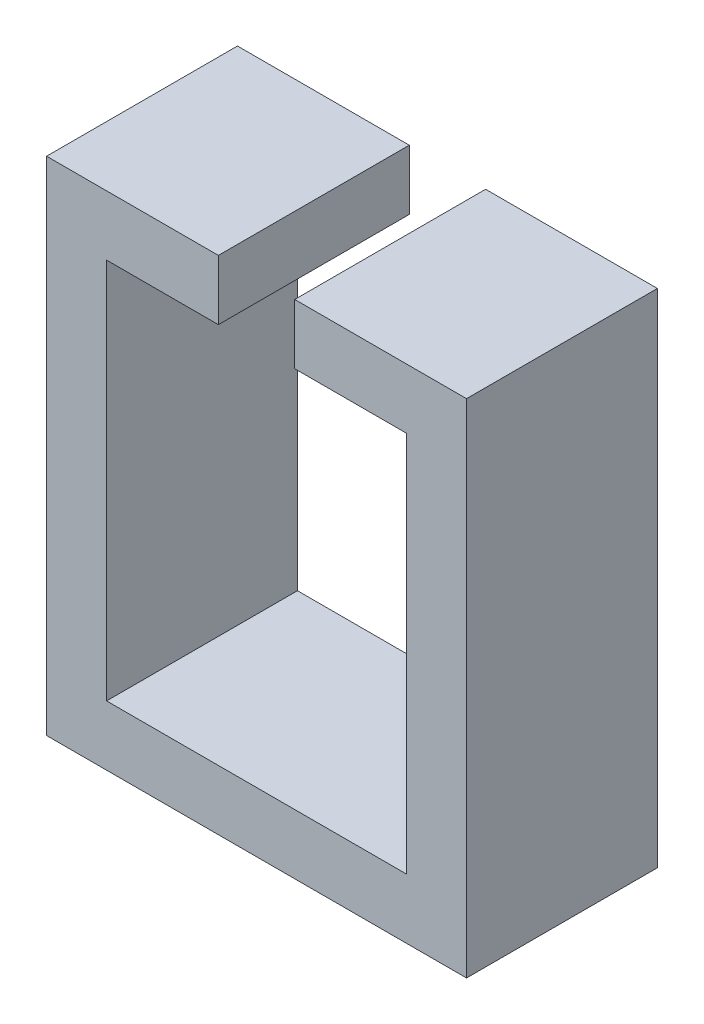
SolidWorks part; units mm, degrees
ref_plane "정면" through (0, 0, 0) normal (0, 0, 1) x (1, 0, 0)
ref_plane "윗면" through (0, 0, 0) normal (0, 1, 0) x (1, 0, 0)
ref_plane "우측면" through (0, 0, 0) normal (1, 0, 0) x (0, 0, -1)
sketch "스케치1" plane through (0, 0, 0) normal (0, 0, 1) x (1, 0, 0)
  line L0 (0.7, 3.5) -> (2.75, 3.5)
  line L1 (-3.85, 4.6) -> (-0.7, 4.6)
  line L2 (-3.85, 4.6) -> (-3.85, -4.6)
  line L3 (-3.85, -4.6) -> (3.85, -4.6)
  line L4 (3.85, 4.6) -> (3.85, -4.6)
  line L5 (-3.85, 4.6) -> (3.85, -4.6) construction
  line L6 (-3.85, -4.6) -> (3.85, 4.6) construction
  line L7 (-2.75, 3.5) -> (-0.7, 3.5)
  line L8 (-2.75, 3.5) -> (-2.75, -3.5)
  line L9 (-2.75, -3.5) -> (2.75, -3.5)
  line L10 (2.75, 3.5) -> (2.75, -3.5)
  line L11 (-2.75, 3.5) -> (2.75, -3.5) construction
  line L12 (-2.75, -3.5) -> (2.75, 3.5) construction
  line L14 (-0.7, 4.6) -> (-0.7, 3.5)
  line L15 (0.7, 4.6) -> (3.85, 4.6)
  line L16 (0.7, 4.6) -> (0.7, 3.5)
  point P0 (0, 0)
  point P5 (0, 0)
  dimension "D1" = 9.2
  dimension "D2" = 7.7
  dimension "D3" = 5.5
  dimension "D4" = 7
  dimension "D5" = 2.05
  dimension "D6" = 2.05
extrude "보스-돌출1" add sketch "스케치1" along normal blind 3.5
